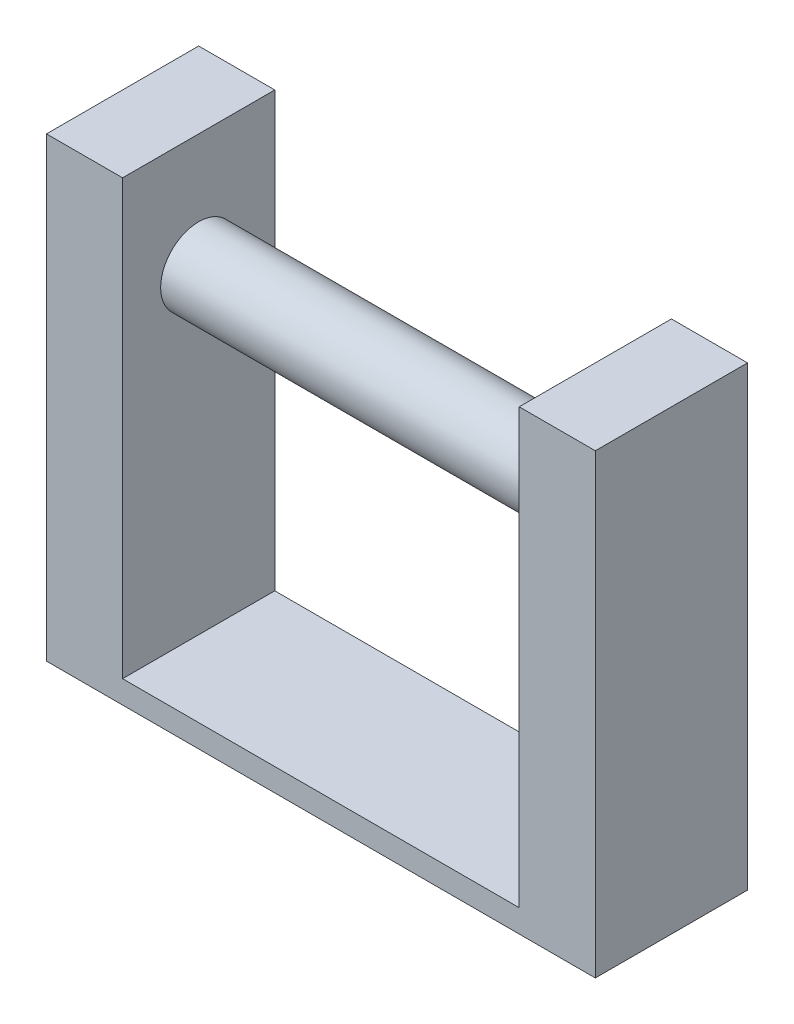
SolidWorks part; units mm, degrees
ref_plane "Front Plane" through (0, 0, 0) normal (0, 0, 1) x (1, 0, 0)
ref_plane "Top Plane" through (0, 0, 0) normal (0, 1, 0) x (1, 0, 0)
ref_plane "Right Plane" through (0, 0, 0) normal (1, 0, 0) x (0, 0, -1)
sketch "Sketch1" plane through (0, 0, 0) normal (0, 0, 1) x (1, 0, 0)
  line L0 (-51.6982, 23.0571) -> (-51.6982, -36.9429)
  line L1 (-51.6982, -36.9429) -> (20.4224, -36.9429)
  line L2 (20.4224, -36.9429) -> (20.4224, 23.0571)
  line L3 (20.4224, 23.0571) -> (10.4224, 23.0571)
  line L4 (10.4224, 23.0571) -> (10.4224, -33.9429)
  line L5 (10.4224, -33.9429) -> (-41.6982, -33.9429)
  line L6 (-41.6982, -33.9429) -> (-41.6982, 23.0571)
  line L7 (-41.6982, 23.0571) -> (-51.6982, 23.0571)
  dimension "D1" = 60
  dimension "D2" = 60
  dimension "D3" = 3
  dimension "D4" = 10
  dimension "D5" = 10
extrude "Boss-Extrude1" add sketch "Sketch1" along normal blind 20
sketch "Sketch2" plane through (20.4224, 0, 0) normal (1, 0, 0) x (0, 0, -1)
  line L0 (-20, 23.0571) -> (0, 23.0571) construction
  circle A0 centre (-10, 8.0571) radius 5
  dimension "D1" = 15
extrude "Boss-Extrude2" add sketch "Sketch2" against normal up to vertex (72.1206 mm away) contours A0
